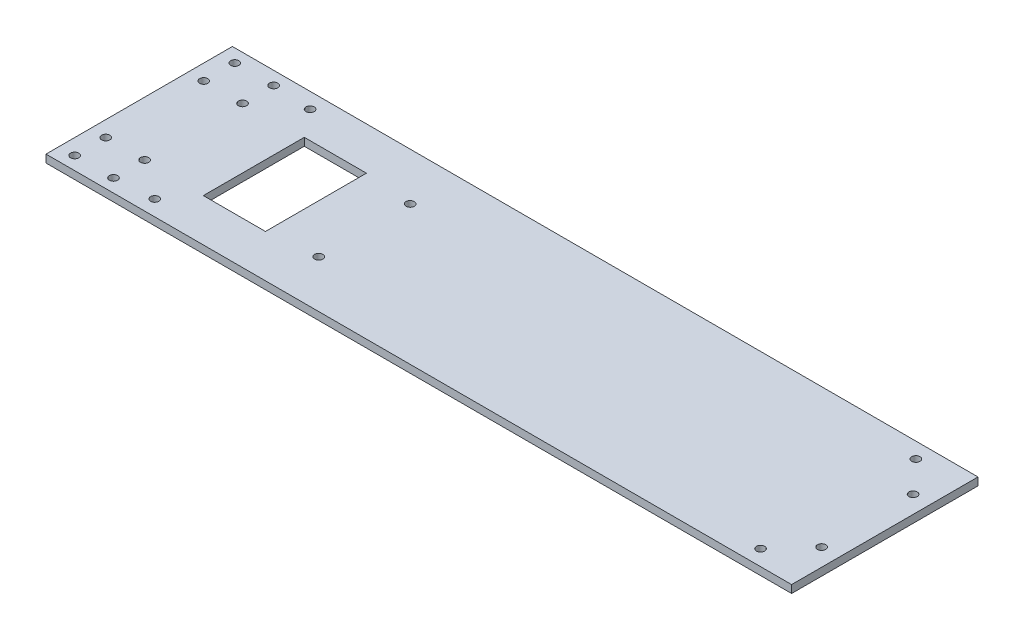
SolidWorks part; units mm, degrees
ref_plane "Front Plane" through (0, 0, 0) normal (0, 0, 1) x (1, 0, 0)
ref_plane "Top Plane" through (0, 0, 0) normal (0, 1, 0) x (1, 0, 0)
ref_plane "Right Plane" through (0, 0, 0) normal (1, 0, 0) x (0, 0, -1)
sketch "Sketch2" plane through (0, 0, 0) normal (0, 1, 0) x (1, 0, 0)
  line L1 (0, 0) -> (609.6, 0)
  line L2 (0, 0) -> (0, 152.4)
  line L3 (0, 152.4) -> (609.6, 152.4)
  line L4 (609.6, 0) -> (609.6, 152.4)
  dimension "D1" = 152.4
  dimension "D2" = 609.6
extrude "Boss-Extrude1" add sketch "Sketch2" along normal blind 6.35
sketch "Sketch3" plane through (0, 6.35, 0) normal (0, 1, 0) x (1, 0, 0)
  line L0 (0, 76.2) -> (609.6, 76.2) construction
  line L1 (144.5006, 34.925) -> (93.7006, 34.925)
  line L2 (144.5006, 34.925) -> (144.5006, 117.475)
  line L3 (144.5006, 117.475) -> (93.7006, 117.475)
  line L4 (93.7006, 34.925) -> (93.7006, 117.475)
  line L5 (0, 152.4) -> (0, 0) construction
  line L6 (609.6, 0) -> (609.6, 152.4) construction
  point P5 (119.1006, 117.475)
  point P11 (93.7006, 76.2)
  dimension "D1" = 50.8
  dimension "D2" = 119.1006
  dimension "D3" = 82.55
extrude "Cut-Extrude1" cut sketch "Sketch3" against normal up to next
sketch "Sketch4" plane through (0, 6.35, 0) normal (0, 1, 0) x (1, 0, 0)
  line L0 (571.5, 152.4) -> (571.5, 139.7) construction
  line L1 (609.6, 152.4) -> (0, 152.4) construction
  line L2 (571.5, 0) -> (571.5, 12.7) construction
  line L3 (0, 0) -> (609.6, 0) construction
  line L4 (609.6, 0) -> (609.6, 152.4) construction
  line L5 (76.2, 0) -> (76.2, 12.7) construction
  line L6 (76.2, 152.4) -> (76.2, 139.7) construction
  line L7 (0, 152.4) -> (0, 0) construction
  circle A0 centre (571.5, 12.7) radius 3.3782
  circle A1 centre (571.5, 139.7) radius 3.3782
  circle A2 centre (76.2, 12.7) radius 3.3782
  circle A4 centre (76.2, 139.7) radius 3.3782
  dimension "D1" = 6.7564
  dimension "D2" = 12.7
  dimension "D3" = 38.1
  dimension "D4" = 76.2
extrude "Cut-Extrude2" cut sketch "Sketch4" against normal through all
sketch "Sketch5" plane through (0, 6.35, 0) normal (0, 1, 0) x (1, 0, 0)
  line L0 (609.6, 113.5878) -> (0, 113.5878) construction
  line L1 (609.6, 0) -> (609.6, 152.4) construction
  line L2 (0, 152.4) -> (0, 0) construction
  line L3 (0, 38.8122) -> (609.6, 38.8122) construction
  line L4 (609.6, 76.2) -> (0, 76.2) construction
  line L5 (595.3125, 113.5878) -> (595.3125, 38.8122) construction
  line L6 (184.15, 113.5878) -> (184.15, 38.8122) construction
  circle A0 centre (595.3125, 113.5878) radius 3.3782
  circle A1 centre (595.3125, 38.8122) radius 3.3782
  circle A2 centre (184.15, 38.8122) radius 3.3782
  circle A3 centre (184.15, 113.5878) radius 3.3782
  point P14 (595.3125, 76.2)
  dimension "D2" = 6.7564
  dimension "D1" = 14.2875
  dimension "D3" = 74.7756
  dimension "D4" = 425.45
extrude "Cut-Extrude3" cut sketch "Sketch5" against normal through all
sketch "Sketch6" plane through (0, 6.35, 0) normal (0, 1, 0) x (1, 0, 0)
  line L0 (12.7, 23.4493) -> (44.45, 23.4493) construction
  line L1 (0, 152.4) -> (0, 0) construction
  line L2 (44.45, 36.1493) -> (44.45, 10.7493) construction
  line L3 (12.7, 36.1493) -> (12.7, 10.7493) construction
  line L4 (12.7, 128.9507) -> (44.45, 128.9507) construction
  line L5 (44.45, 141.6507) -> (44.45, 116.2507) construction
  line L6 (12.7, 141.6507) -> (12.7, 116.2507) construction
  line L7 (0, 76.2) -> (28.575, 76.2) construction
  line L8 (28.575, 23.4493) -> (28.575, 128.9507) construction
  circle A0 centre (12.7, 36.1493) radius 3.3782
  circle A1 centre (12.7, 10.7493) radius 3.3782
  circle A2 centre (44.45, 10.7493) radius 3.3782
  circle A3 centre (44.45, 36.1493) radius 3.3782
  circle A4 centre (12.7, 141.6507) radius 3.3782
  circle A5 centre (12.7, 116.2507) radius 3.3782
  circle A6 centre (44.45, 116.2507) radius 3.3782
  circle A7 centre (44.45, 141.6507) radius 3.3782
  point P6 (44.45, 23.4493)
  point P9 (12.7, 23.4493)
  point P18 (44.45, 128.9507)
  point P21 (12.7, 128.9507)
  point P30 (28.575, 76.2)
  dimension "D4" = 6.7564
  dimension "D7" = 40.0507
  dimension "D1" = 31.75
  dimension "D2" = 28.575
  dimension "D3" = 25.4
extrude "Cut-Extrude4" cut sketch "Sketch6" against normal through all
